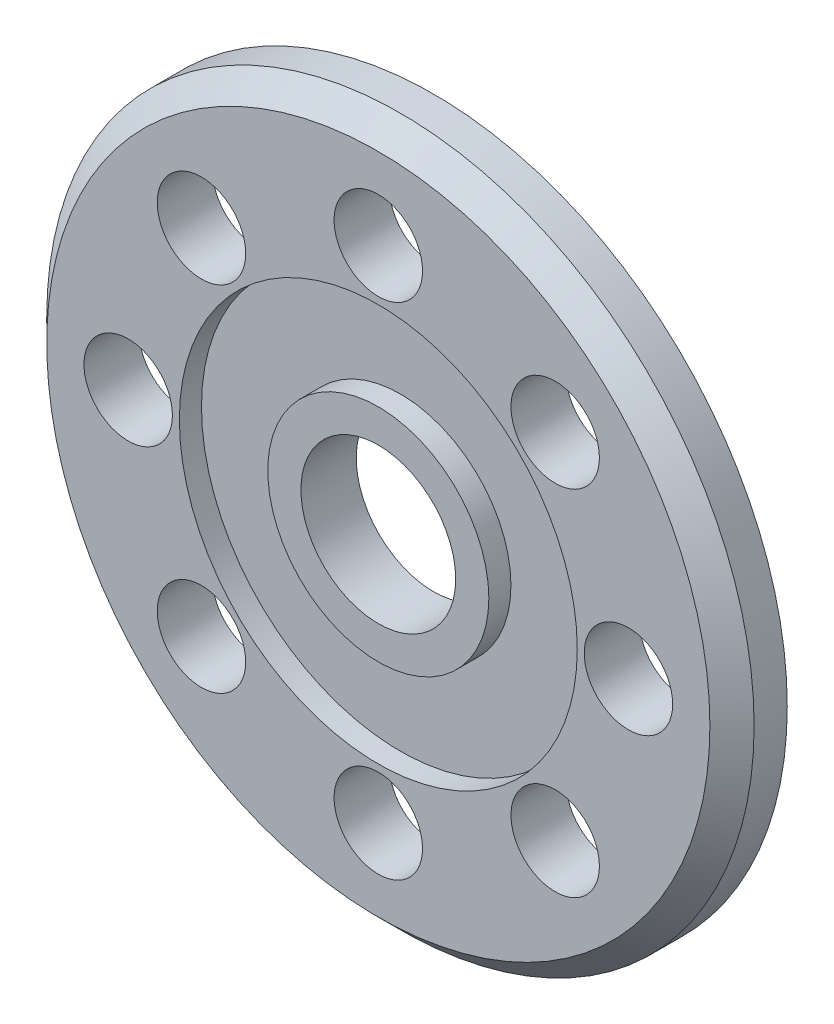
SolidWorks part; units mm, degrees
ref_plane "Front Plane" through (0, 0, 0) normal (0, 0, 1) x (1, 0, 0)
ref_plane "Top Plane" through (0, 0, 0) normal (0, 1, 0) x (1, 0, 0)
ref_plane "Right Plane" through (0, 0, 0) normal (1, 0, 0) x (0, 0, -1)
sketch "Sketch1" plane through (0, 0, 0) normal (0, 0, 1) x (1, 0, 0)
  circle A0 centre (0, 0) radius 11.315 construction
  circle A1 centre (0, 11.315) radius 2
  circle A2 centre (8.0009, 8.0009) radius 2
  circle A3 centre (11.315, 0) radius 2
  circle A4 centre (8.0009, -8.0009) radius 2
  circle A5 centre (0, -11.315) radius 2
  circle A6 centre (-8.0009, -8.0009) radius 2
  circle A7 centre (-11.315, 0) radius 2
  circle A8 centre (-8.0009, 8.0009) radius 2
  circle A9 centre (0, 0) radius 16
  circle A10 centre (0, 0) radius 3.5
  circle A11 centre (0, 0) radius 9 construction
  point P21 (0, 0)
  dimension "D1" = 22.63
  dimension "D2" = 4
  dimension "D4" = 32
  dimension "D5" = 7
  dimension "D6" = 18
  dimension "D3" = 8
extrude "Boss-Extrude1" add sketch "Sketch1" along normal blind 2.5
sketch "Sketch2" plane through (0, 0, 2.5) normal (0, 0, 1) x (1, 0, 0)
  circle A0 centre (0, 0) radius 9 construction
  circle A1 centre (0, 0) radius 9
  circle A2 centre (0, 0) radius 5
  dimension "D1" = 10
extrude "Cut-Extrude1" cut sketch "Sketch2" against normal blind 1
chamfer "Chamfer1" distance 1 angle 45 1 edges at (16, 0, 2.5)
